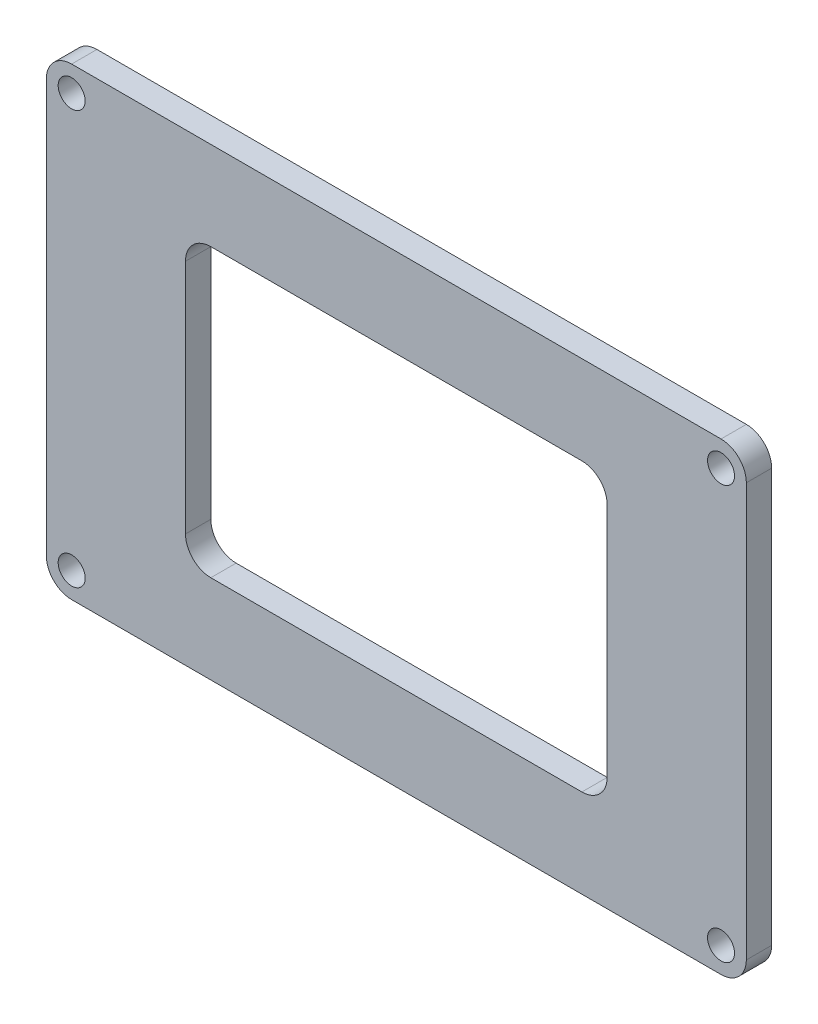
SolidWorks part; units mm, degrees
ref_plane "前视基准面" through (0, 0, 0) normal (0, 0, 1) x (1, 0, 0)
ref_plane "上视基准面" through (0, 0, 0) normal (0, 1, 0) x (1, 0, 0)
ref_plane "右视基准面" through (0, 0, 0) normal (1, 0, 0) x (0, 0, -1)
other "Configuration Table"
sketch "草图1" plane through (0, 0, 0) normal (0, 0, 1) x (1, 0, 0)
  line L0 (38.5, 3) -> (38.5, -57.9371) construction
  line L1 (0, -52) -> (77, -52)
  line L2 (-3, -49) -> (-3, 0)
  line L3 (0, 3) -> (77, 3)
  line L4 (80, -49) -> (80, 0)
  line L5 (80, -24.5) -> (-16.7766, -24.5) construction
  line L7 (16.5, -41.5) -> (60.5, -41.5)
  line L8 (13.5, -38.5) -> (13.5, -10.5)
  line L9 (16.5, -7.5) -> (60.5, -7.5)
  line L10 (63.5, -38.5) -> (63.5, -10.5)
  line L11 (13.5, -41.5) -> (63.5, -7.5) construction
  line L12 (13.5, -7.5) -> (63.5, -41.5) construction
  circle A0 centre (0, 0) radius 1.6
  circle A1 centre (77, 0) radius 1.6
  circle A2 centre (0, -49) radius 1.6
  circle A3 centre (77, -49) radius 1.6
  arc A4 (0, -52) -> (-3, -49) centre (0, -49) cw
  arc A5 (77, -52) -> (80, -49) centre (77, -49) ccw
  arc A6 (77, 3) -> (80, 0) centre (77, 0) cw
  arc A7 (-3, 0) -> (0, 3) centre (0, 0) cw
  arc A8 (16.5, -41.5) -> (13.5, -38.5) centre (16.5, -38.5) cw
  arc A9 (60.5, -41.5) -> (63.5, -38.5) centre (60.5, -38.5) ccw
  arc A10 (60.5, -7.5) -> (63.5, -10.5) centre (60.5, -10.5) cw
  arc A11 (13.5, -10.5) -> (16.5, -7.5) centre (16.5, -10.5) cw
  point P11 (-3, -52)
  point P20 (80, 3)
  point P23 (-3, 3)
  point P27 (38.5, -24.5)
  point P33 (38.5, 3)
  point P34 (80, -24.5)
  dimension "D1" = 3.2
  dimension "D2" = 3.2
  dimension "D3" = 3.2
  dimension "D4" = 3.2
  dimension "D9" = 3
  dimension "D14" = 3
  dimension "D5" = 49
  dimension "D6" = 77
  dimension "D7" = 83
  dimension "D8" = 55
  dimension "D10" = 3
  dimension "D11" = 3
  dimension "D12" = 50
  dimension "D13" = 34
extrude "凸台-拉伸1" add sketch "草图1" along normal blind 3
